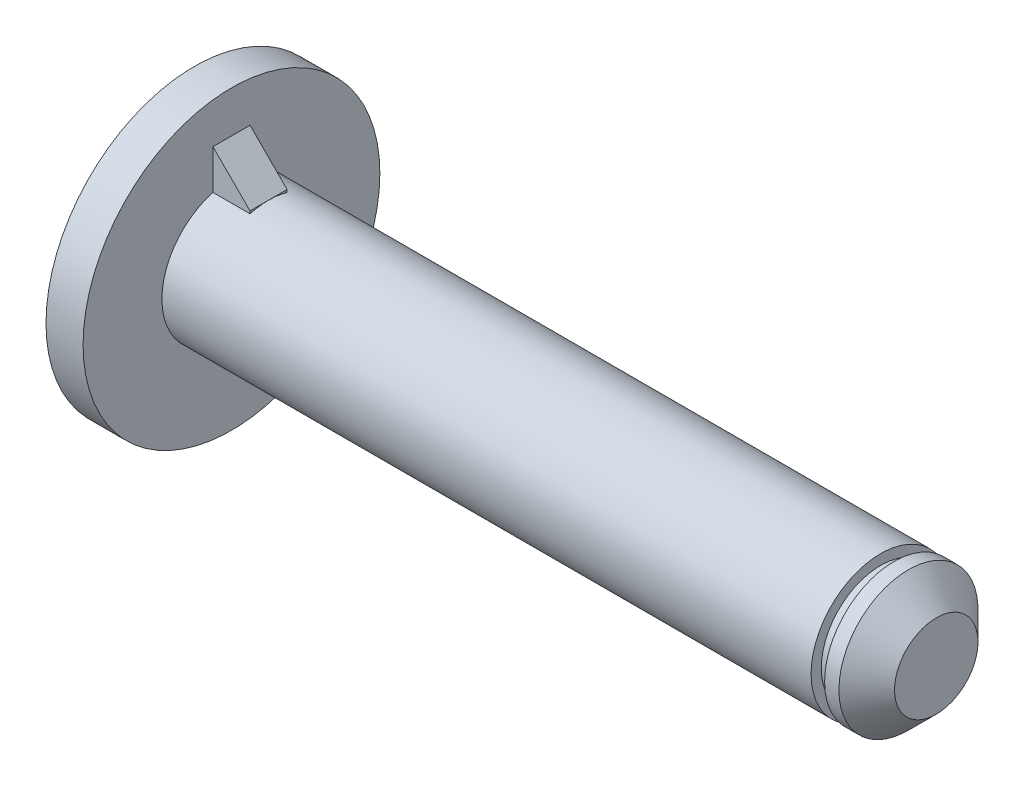
SolidWorks part; units mm, degrees
material "AISI 1035 Steel (SS)"
ref_plane "Front Plane" through (0, 0, 0) normal (0, 0, 1) x (1, 0, 0)
ref_plane "Top Plane" through (0, 0, 0) normal (0, 1, 0) x (1, 0, 0)
ref_plane "Right Plane" through (0, 0, 0) normal (1, 0, 0) x (0, 0, -1)
sketch "Sketch1" plane through (0, 0, 0) normal (0, 0, 1) x (1, 0, 0)
  line L0 (-20, 0) -> (20, 0) construction
  line L1 (-20, 0) -> (-20, 8)
  line L2 (-20, 8) -> (-18, 8)
  line L3 (-18, 8) -> (-18, 3.75)
  line L4 (-18, 3.75) -> (17, 3.75)
  line L5 (17, 3.75) -> (17, 3.2)
  line L6 (17, 3.2) -> (17.73, 3.2)
  line L7 (17.73, 3.2) -> (17.73, 3.75)
  line L8 (17.73, 3.75) -> (20, 3.75)
  line L9 (20, 3.75) -> (20, 0)
  line L10 (-20, 0) -> (20, 0)
  dimension "D1" = 40
  dimension "D2" = 0.73
  dimension "D3" = 6.4
  dimension "D4" = 7.5
  dimension "D5" = 3
  dimension "D6" = 2
  dimension "D7" = 16
revolve "Main Body" add sketch "Sketch1" angle 360 about L0
sketch "Sketch2" plane through (0, 0, 0) normal (0, 0, 1) x (1, 0, 0)
  line L0 (-18, 5.75) -> (-16, 3.75)
  line L1 (-18, -8) -> (-18, 8) construction
  line L2 (17, 3.75) -> (-18, 3.75) construction
  line L3 (-16, 3.75) -> (-16, 2.75)
  line L4 (-16, 2.75) -> (-19, 2.75)
  line L5 (-19, 2.75) -> (-19, 5.75)
  line L6 (-19, 5.75) -> (-18, 5.75)
  dimension "D1" = 1
  dimension "D2" = 1
  dimension "D3" = 2
  dimension "D4" = 2
extrude "Rib" add sketch "Sketch2" along normal mid plane 2
chamfer "Chamfer1" distance 1.5 angle 45 1 edges at (20, 0, 3.75)
